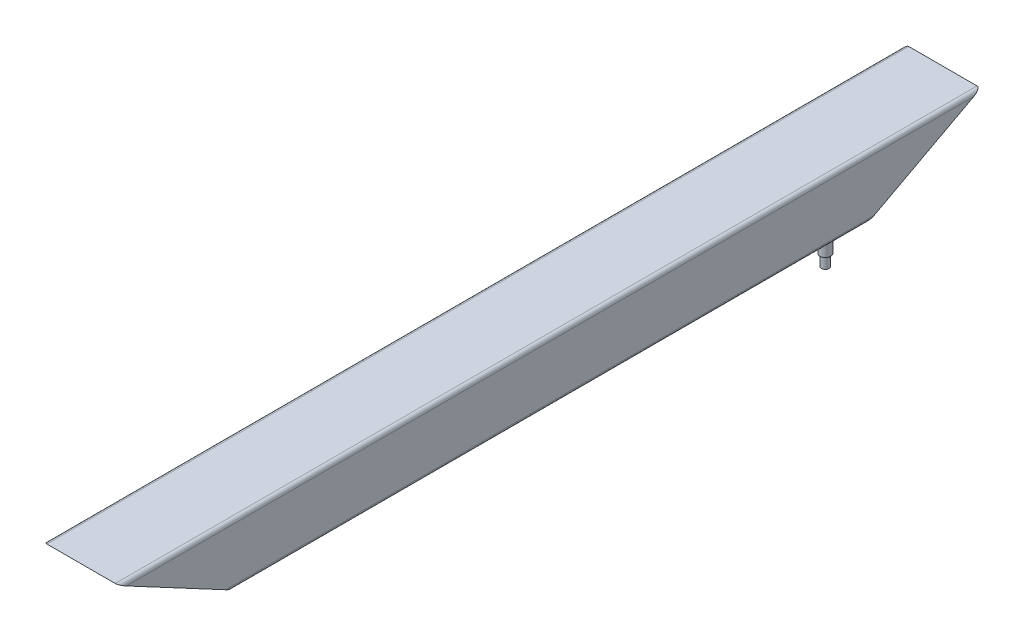
SolidWorks part; units mm, degrees
material "Structural Steel"
ref_plane "Piano frontale" through (0, 0, 0) normal (0, 0, 1) x (1, 0, 0)
ref_plane "Piano superiore" through (0, 0, 0) normal (0, 1, 0) x (1, 0, 0)
ref_plane "Piano destro" through (0, 0, 0) normal (1, 0, 0) x (0, 0, -1)
sketch "Schizzo1" plane through (0, 0, 0) normal (0, 0, 1) x (1, 0, 0)
  line L1 (5, 0) -> (95, 0)
  line L2 (0, 5) -> (0, 75)
  line L3 (5, 80) -> (95, 80)
  line L4 (100, 5) -> (100, 75)
  arc A0 (0, 75) -> (5, 80) centre (5, 75) cw
  arc A1 (95, 80) -> (100, 75) centre (95, 75) cw
  arc A2 (95, 0) -> (100, 5) centre (95, 5) ccw
  arc A3 (5, 0) -> (0, 5) centre (5, 5) cw
  point P7 (0, 80)
  point P12 (100, 0)
  point P15 (0, 0)
  dimension "D3" = 5
  dimension "D1" = 100
  dimension "D2" = 80
extrude "Estrusione-Sottile1" add sketch "Schizzo1" along normal blind 1200 thin
sketch "Schizzo2" plane through (100, 0, 0) normal (1, 0, 0) x (0, 0, -1)
  line L0 (-1050, 181.1521) -> (-1050, -156.5272) construction
  line L1 (-1200, 5) -> (-1200, 75) construction
  line L2 (-214, 163.6994) -> (-214, -110.5533) construction
  line L3 (-1200, 80) -> (-1050, 0)
  line L4 (-1050, 0) -> (-1200, 0)
  line L5 (-1200, 0) -> (-1200, 80)
  line L6 (-64, 157.8086) -> (-64, -67.0058) construction
  line L7 (-64, 80) -> (-214, 0)
  line L8 (-1200, 80) -> (0, 80) construction
  line L9 (-1200, 0) -> (0, 0) construction
  line L10 (-214, 0) -> (0, 0)
  line L11 (0, 0) -> (0, 80)
  line L12 (0, 80) -> (-64, 80)
  dimension "D1" = 150
  dimension "D2" = 836
  dimension "D3" = 150
extrude "Estrusione1" cut sketch "Schizzo2" against normal through all
sketch "Schizzo3" plane through (0, 0, 0) normal (0, -1, 0) x (1, 0, 0)
  line L0 (5, 64) -> (95, 64) construction
  line L1 (0, 1059.375) -> (0, 204.625) construction
  circle A0 centre (10, 354) radius 3.4
  dimension "D1" = 6.8
  dimension "D3" = 10
  dimension "D2" = 290
extrude "Taglio-Estrusione1" cut sketch "Schizzo3" against normal blind 10
cosmetic thread "Filettatura cosmetica4" parameters "D2"=8
pattern_linear "Ripetizione a L1" count 2 spacing 40 along (1, 0, 0) count 2 spacing 36 along (0, 0, 1) of "Taglio-Estrusione1"
cosmetic thread "Filettatura cosmetica1" parameters "D2"=8
cosmetic thread "Filettatura cosmetica2" parameters "D2"=8
cosmetic thread "Filettatura cosmetica3" parameters "D2"=8
sketch "Schizzo4" plane through (0, 0, 0) normal (0, -1, 0) x (1, 0, 0)
  line L0 (5, 64) -> (95, 64) construction
  line L1 (100, 1059.375) -> (100, 204.625) construction
  circle A0 centre (88, 257) radius 7
  dimension "D3" = 14
  dimension "D1" = 193
  dimension "D2" = 12
extrude "Estrusione-Estrusione1" add sketch "Schizzo4" along normal blind 18
sketch "Schizzo5" plane through (0, -18, 0) normal (0, -1, 0) x (1, 0, 0)
  circle A0 centre (88, 257) radius 5
  dimension "D1" = 10
extrude "Estrusione-Estrusione2" add sketch "Schizzo5" along normal blind 15
cosmetic thread "Filettatura cosmetica5" parameters "D2"=8.344
